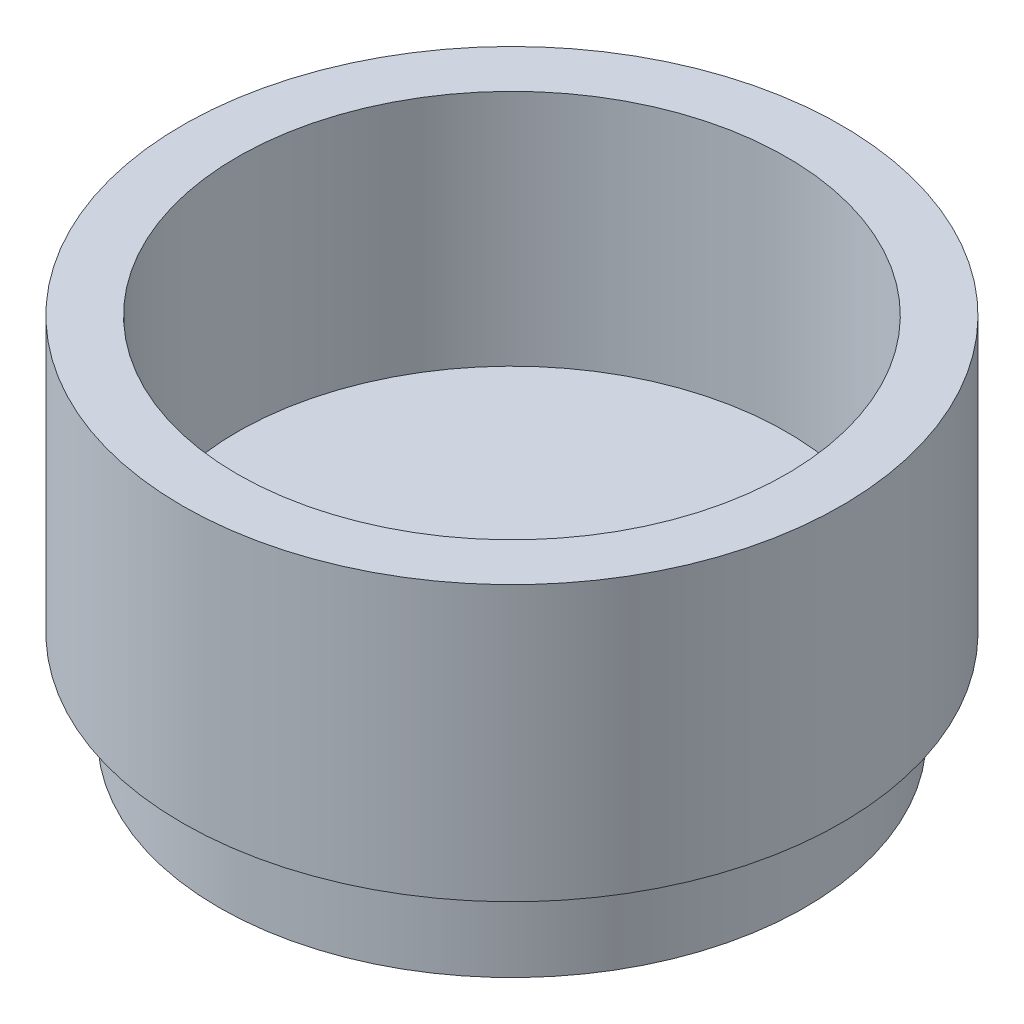
SolidWorks part; units mm, degrees
ref_plane "Front Plane" through (0, 0, 0) normal (0, 0, 1) x (1, 0, 0)
ref_plane "Top Plane" through (0, 0, 0) normal (0, 1, 0) x (1, 0, 0)
ref_plane "Right Plane" through (0, 0, 0) normal (1, 0, 0) x (0, 0, -1)
sketch "Sketch1" plane through (0, 0, 0) normal (0, 1, 0) x (1, 0, 0)
  circle A0 centre (0, 0) radius 160
extrude "Boss-Extrude1" add sketch "Sketch1" along normal blind 50
sketch "Sketch2" plane through (0, 50, 0) normal (0, 1, 0) x (1, 0, 0)
  circle A0 centre (0, 0) radius 180
extrude "Boss-Extrude2" add sketch "Sketch2" along normal blind 150
sketch "Sketch3" plane through (0, 200, 0) normal (0, 1, 0) x (1, 0, 0)
  circle A0 centre (0, 0) radius 150
extrude "Cut-Extrude1" cut sketch "Sketch3" against normal blind 130
